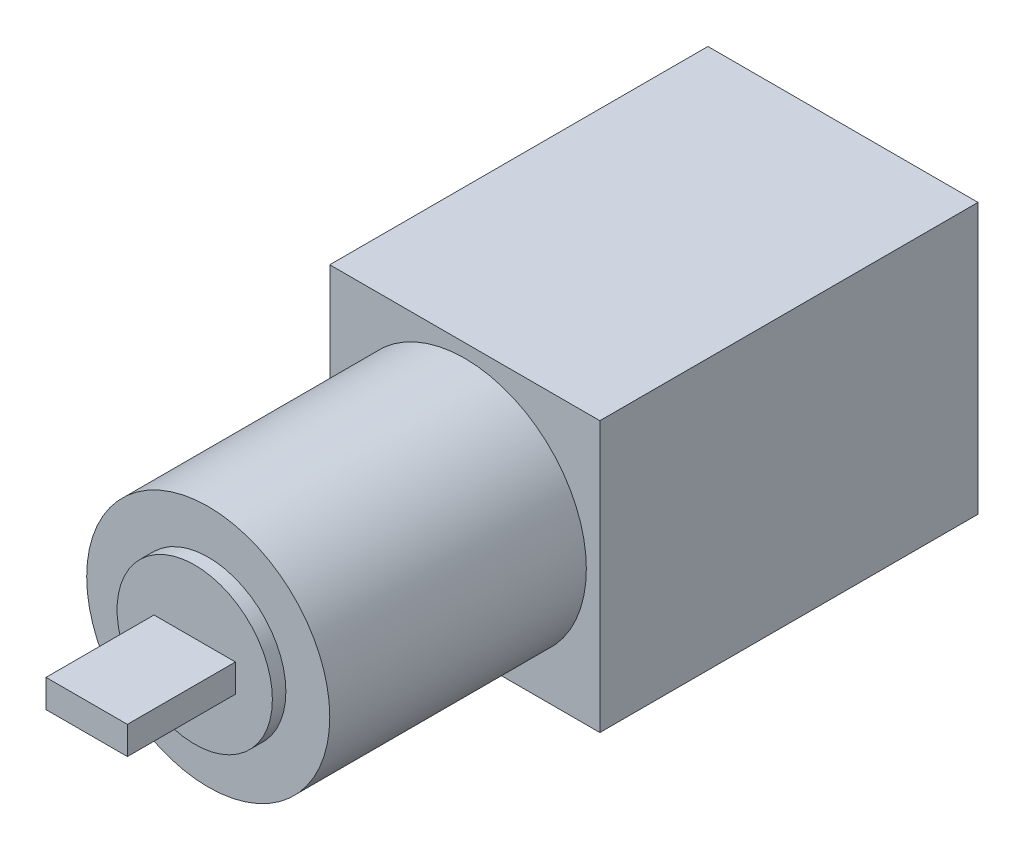
SolidWorks part; units mm, degrees
ref_plane "Plan de face" through (0, 0, 0) normal (0, 0, 1) x (1, 0, 0)
ref_plane "Plan de dessus" through (0, 0, 0) normal (0, 1, 0) x (1, 0, 0)
ref_plane "Plan de droite" through (0, 0, 0) normal (1, 0, 0) x (0, 0, -1)
sketch "Esquisse1" plane through (0, 0, 0) normal (0, 0, 1) x (1, 0, 0)
  line L1 (0, 0) -> (40, 0)
  line L2 (0, 0) -> (0, 40)
  line L3 (0, 40) -> (40, 40)
  line L4 (40, 0) -> (40, 40)
  point P0 (0, 0)
other "Esquisse au crayon1" parameters "D1"=60.917, "D2"=40.6041
extrude "Boss.-Extru.1" add sketch "Esquisse1" along normal blind 56
sketch "Esquisse2" plane through (0, 0, 56) normal (0, 0, 1) x (1, 0, 0)
  line L0 (0, 40) -> (0, 0) construction
  line L1 (40, 40) -> (0, 40) construction
  circle A0 centre (20, 20) radius 18
  point P2 (0, 20)
  point P3 (20, 40)
  point P6 (20.8543, 20.1799)
  point P7 (20, 40)
  point P10 (20.8543, 20.1799)
  point P11 (20.8543, 20.1799)
  point P12 (20.8543, 20.1799)
  dimension "D1" = 36
extrude "Boss.-Extru.2" add sketch "Esquisse2" along normal blind 38
sketch "Esquisse3" plane through (0, 0, 94) normal (0, 0, 1) x (1, 0, 0)
  line L0 (0, 40) -> (0, 0) construction
  line L1 (40, 40) -> (0, 40) construction
  circle A0 centre (20, 20) radius 11.5
  point P2 (0, 20)
  point P3 (20, 40)
  point P6 (20, 40.0537)
  point P9 (20, 20)
  point P10 (0, 0)
  dimension "D1" = 23
extrude "Boss.-Extru.3" add sketch "Esquisse3" along normal blind 2
sketch "Esquisse4" plane through (0, 0, 96) normal (0, 0, 1) x (1, 0, 0)
  line L1 (13.9749, 22.0683) -> (26.0251, 22.0683)
  line L2 (13.9749, 22.0683) -> (13.9749, 17.9317)
  line L3 (13.9749, 17.9317) -> (26.0251, 17.9317)
  line L4 (26.0251, 22.0683) -> (26.0251, 17.9317)
  point P4 (20, 20)
  point P5 (26.0251, 20)
  point P7 (20, 22.0683)
extrude "Boss.-Extru.4" add sketch "Esquisse4" along normal blind 16
